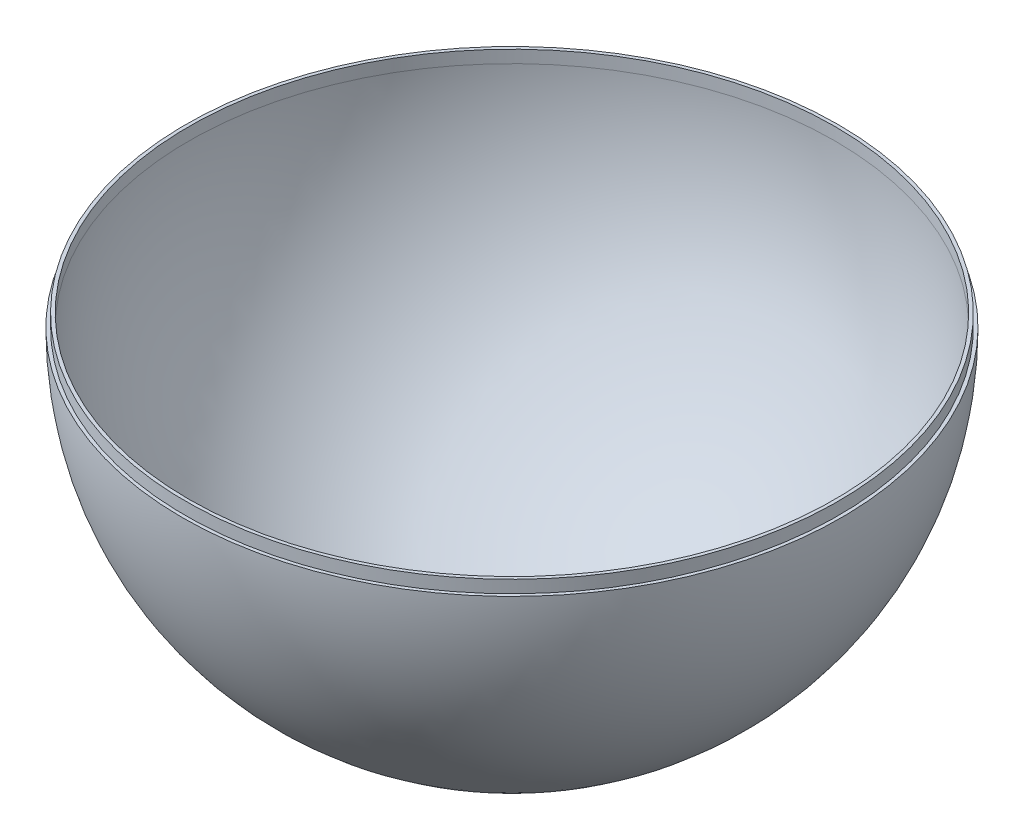
SolidWorks part; units mm, degrees
material "PMMA"
ref_plane "Front Plane" through (0, 0, 0) normal (0, 0, 1) x (1, 0, 0)
ref_plane "Top Plane" through (0, 0, 0) normal (0, 1, 0) x (1, 0, 0)
ref_plane "Right Plane" through (0, 0, 0) normal (1, 0, 0) x (0, 0, -1)
sketch "Sketch1" plane through (0, 0, 0) normal (0, 1, 0) x (1, 0, 0)
  line L0 (0, 100) -> (0, -100)
  arc A0 (0, -100) -> (0, 100) centre (0, 0) ccw
  dimension "D1" = 200
revolve "Revolve1" add sketch "Sketch1" angle 360 about L0
shell "Shell1" thickness 2
sketch "Sketch2" plane through (0, 0, 0) normal (0, 1, 0) x (1, 0, 0)
  circle A0 centre (0, 0) radius 125.7202
extrude "Cut-Extrude1" cut sketch "Sketch2" along normal blind 156
sketch "Sketch3" plane through (0, 0, 0) normal (0, 1, 0) x (1, 0, 0)
  circle A1 centre (0, 0) radius 98 construction
  circle A2 centre (0, 0) radius 99
  circle A3 centre (0, 0) radius 99
  circle A4 centre (0, 0) radius 98
  dimension "D1" = 1
extrude "Boss-Extrude1" add sketch "Sketch3" along normal blind 3.8
